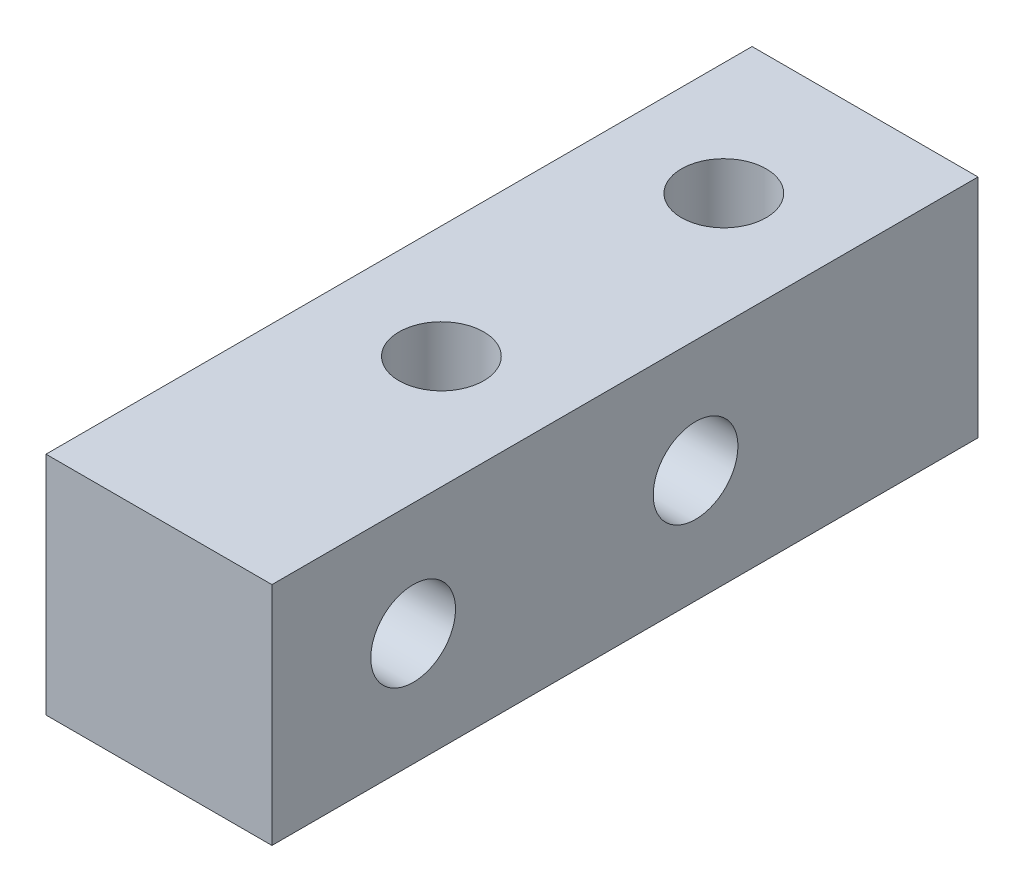
SolidWorks part; units mm, degrees
material "6061 合金"
ref_plane "前视基准面" through (0, 0, 0) normal (0, 0, 1) x (1, 0, 0)
ref_plane "上视基准面" through (0, 0, 0) normal (0, 1, 0) x (1, 0, 0)
ref_plane "右视基准面" through (0, 0, 0) normal (1, 0, 0) x (0, 0, -1)
other "Configuration Table"
sketch "草图1" plane through (0, 0, 0) normal (0, 0, 1) x (1, 0, 0)
  line L1 (0, 0) -> (8, 0)
  line L2 (0, 0) -> (0, 8)
  line L3 (0, 8) -> (8, 8)
  line L4 (8, 0) -> (8, 8)
  dimension "D1" = 8
  dimension "D2" = 8
extrude "凸台-拉伸1" add sketch "草图1" along normal blind 25
sketch "草图2" plane through (0, 8, 0) normal (0, 1, 0) x (1, 0, 0)
  line L0 (4, 0) -> (4, -25) construction
  line L1 (8, 0) -> (0, 0) construction
  line L2 (8, -25) -> (0, -25) construction
  circle A0 centre (4, -5) radius 1.5
  circle A1 centre (4, -15) radius 1.5
  dimension "D1" = 3
  dimension "D2" = 3
  dimension "D3" = 5
  dimension "D4" = 10
extrude "切除-拉伸1" cut sketch "草图2" against normal blind 21
sketch "草图3" plane through (8, 0, 0) normal (1, 0, 0) x (0, 0, -1)
  line L0 (-25, 4) -> (0, 4) construction
  line L1 (-25, 0) -> (-25, 8) construction
  line L2 (0, 0) -> (0, 8) construction
  circle A0 centre (-20, 4) radius 1.5
  circle A1 centre (-10, 4) radius 1.5
  dimension "D1" = 3
  dimension "D2" = 5
  dimension "D3" = 10
extrude "切除-拉伸2" cut sketch "草图3" against normal blind 21
